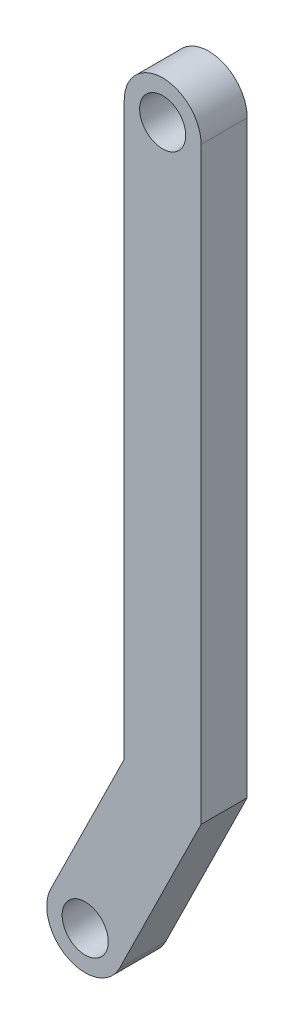
SolidWorks part; units mm, degrees
ref_plane "Front Plane" through (0, 0, 0) normal (0, 0, 1) x (1, 0, 0)
ref_plane "Top Plane" through (0, 0, 0) normal (0, 1, 0) x (1, 0, 0)
ref_plane "Right Plane" through (0, 0, 0) normal (1, 0, 0) x (0, 0, -1)
sketch "Sketch1" plane through (0, 0, 0) normal (0, 0, 1) x (1, 0, 0)
  line L0 (-36.0541, 459.6884) -> (-36.0541, 82.4884) construction
  line L1 (-36.0541, 82.4884) -> (-86.4486, -19.6566) construction
  line L2 (-61.0541, 459.6884) -> (-61.0541, 88.3199)
  line L3 (-61.0541, 88.3199) -> (-108.8685, -8.5955)
  line L4 (-11.0541, 459.6884) -> (-11.0541, 76.6569)
  line L5 (-11.0541, 76.6569) -> (-64.0287, -30.7177)
  circle A0 centre (-36.0541, 459.6884) radius 15
  circle A1 centre (-86.4486, -19.6566) radius 15
  arc A2 (-61.0541, 459.6884) -> (-11.0541, 459.6884) centre (-36.0541, 459.6884) cw
  arc A3 (-108.8685, -8.5955) -> (-64.0287, -30.7177) centre (-86.4486, -19.6566) ccw
  dimension "D3" = 30
  dimension "D4" = 30
  dimension "D1" = 153.74
  dimension "D2" = 377.2
  dimension "D5" = 113.9
  dimension "D6" = 25
  dimension "D7" = 25
extrude "Boss-Extrude1" add sketch "Sketch1" along normal blind 30
